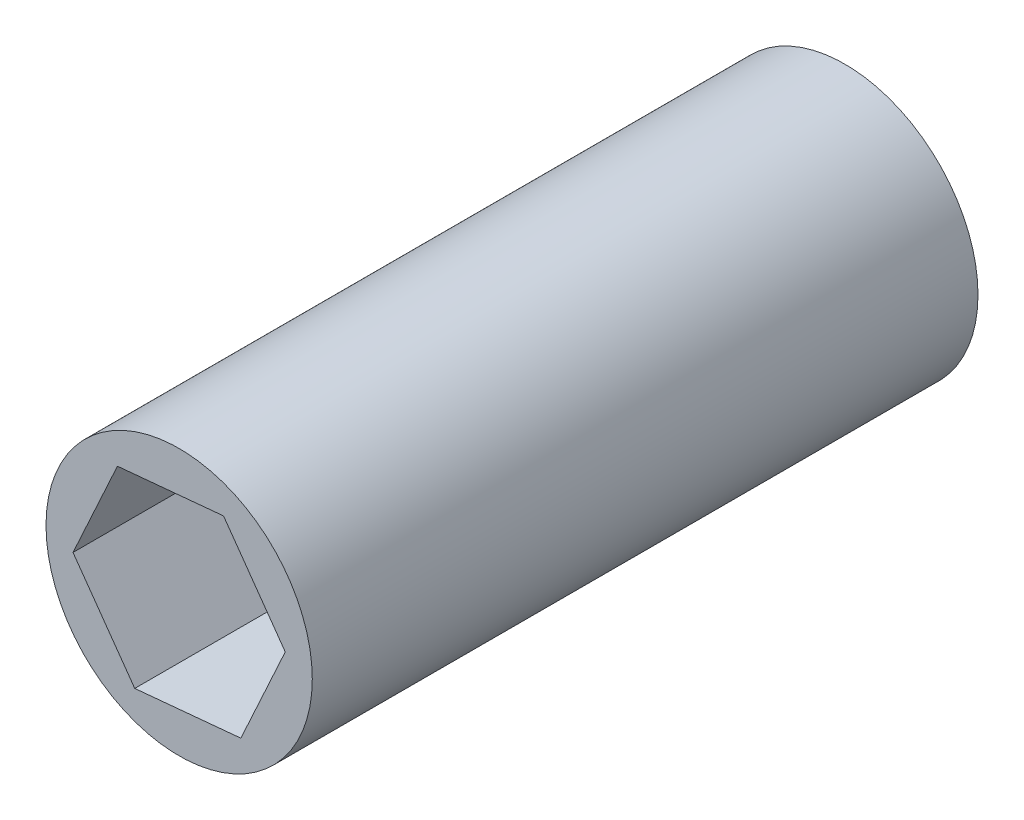
SolidWorks part; units mm, degrees
material "ABS"
ref_plane "Front Plane" through (0, 0, 0) normal (0, 0, 1) x (1, 0, 0)
ref_plane "Top Plane" through (0, 0, 0) normal (0, 1, 0) x (1, 0, 0)
ref_plane "Right Plane" through (0, 0, 0) normal (1, 0, 0) x (0, 0, -1)
sketch "Sketch1" plane through (0, 0, 0) normal (0, 0, 1) x (1, 0, 0)
  line L1 (-4.4153, 6.2174) -> (-7.592, -0.715)
  line L2 (-7.592, -0.715) -> (-3.1768, -6.9324)
  line L3 (-3.1768, -6.9324) -> (4.4153, -6.2174)
  line L4 (4.4153, -6.2174) -> (7.592, 0.715)
  line L5 (7.592, 0.715) -> (3.1768, 6.9324)
  line L6 (3.1768, 6.9324) -> (-4.4153, 6.2174)
  circle A0 centre (0, 0) radius 6.604 construction
  circle A1 centre (0, 0) radius 9.525
  dimension "D2" = 19.05
  dimension "D1" = 13.208
extrude "Boss-Extrude1" add sketch "Sketch1" along normal blind 47.625
